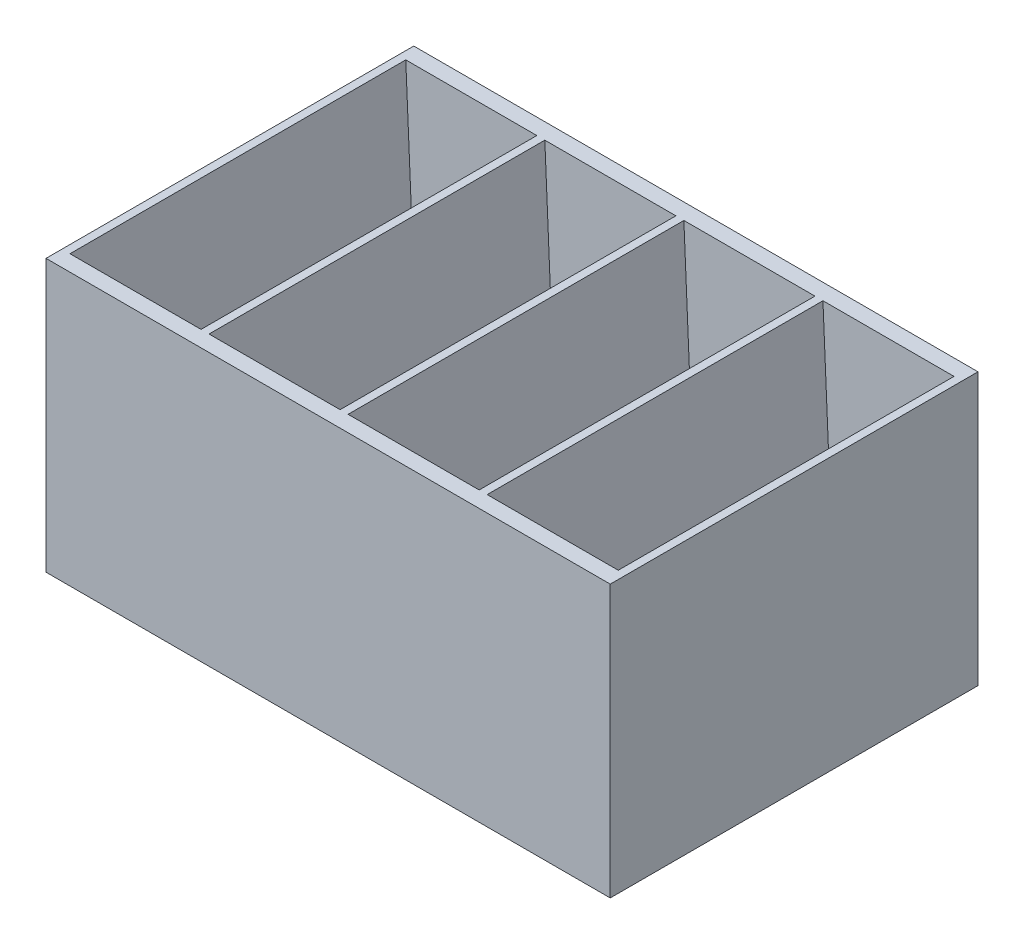
SolidWorks part; units mm, degrees
ref_plane "Front Plane" through (0, 0, 0) normal (0, 0, 1) x (1, 0, 0)
ref_plane "Top Plane" through (0, 0, 0) normal (0, 1, 0) x (1, 0, 0)
ref_plane "Right Plane" through (0, 0, 0) normal (1, 0, 0) x (0, 0, -1)
sketch "Sketch1" plane through (0, 0, 0) normal (0, 0, 1) x (1, 0, 0)
  line L0 (0, 0) -> (0, 107.95)
  line L1 (0, 0) -> (224.0826, 0) construction
  line L2 (0, 0) -> (0, 107.95) construction
  line L3 (0, 107.95) -> (224.0826, 107.95) construction
  line L4 (7.611, 6.35) -> (7.611, 107.95) construction
  line L5 (0, 107.95) -> (3.175, 107.95)
  line L6 (3.175, 107.95) -> (7.611, 6.35)
  line L7 (7.611, 6.35) -> (50.791, 6.35)
  line L8 (50.791, 6.35) -> (55.2269, 107.95)
  line L9 (55.2269, 107.95) -> (55.2269, 0) construction
  line L10 (55.2269, 107.95) -> (58.4019, 107.95)
  line L11 (58.4019, 107.95) -> (58.4019, 0) construction
  line L12 (7.611, 107.95) -> (3.175, 107.95) construction
  line L13 (58.4019, 107.95) -> (62.8379, 6.35)
  line L14 (62.8379, 6.35) -> (106.0179, 6.35)
  line L15 (106.0179, 6.35) -> (110.4538, 107.95)
  line L16 (110.4538, 107.95) -> (113.6288, 107.95)
  line L17 (113.6288, 107.95) -> (118.0648, 6.35)
  line L18 (118.0648, 6.35) -> (161.2448, 6.35)
  line L19 (161.2448, 6.35) -> (165.6807, 107.95)
  line L20 (165.6807, 107.95) -> (168.8557, 107.95)
  line L21 (168.8557, 107.95) -> (173.2917, 6.35)
  line L22 (173.2917, 6.35) -> (216.4717, 6.35)
  line L23 (216.4717, 6.35) -> (220.9076, 107.95)
  line L24 (220.9076, 107.95) -> (224.0826, 107.95)
  line L25 (224.0826, 107.95) -> (224.0826, 0)
  line L26 (224.0826, 0) -> (0, 0)
  line L27 (110.4538, 107.95) -> (110.4538, 0) construction
  line L28 (113.6288, 107.95) -> (113.6288, 0) construction
  line L29 (165.6807, 107.95) -> (165.6807, 0) construction
  line L30 (168.8557, 107.95) -> (168.8557, 0) construction
  line L31 (50.791, 6.35) -> (62.8379, 6.35) construction
  line L32 (106.0179, 6.35) -> (118.0648, 6.35) construction
  line L33 (161.2448, 6.35) -> (173.2917, 6.35) construction
  line L34 (112.0413, 113.03) -> (112.0413, -30.1165) construction
  line L35 (-40.3587, 141.2445) -> (-40.3587, -34.167) construction
  line L36 (264.4413, 143.4606) -> (264.4413, -34.167) construction
  line L37 (50.791, 6.35) -> (50.791, 113.03) construction
  line L38 (92.9913, 151.13) -> (131.0913, 151.13) construction
  line L39 (92.9913, 151.13) -> (92.9913, 113.03) construction
  line L40 (92.9913, 113.03) -> (131.0913, 113.03) construction
  line L41 (131.0913, 151.13) -> (131.0913, 113.03) construction
  line L42 (12.691, 113.03) -> (50.791, 113.03) construction
  line L43 (12.691, 113.03) -> (12.691, 151.13) construction
  line L44 (12.691, 151.13) -> (50.791, 151.13) construction
  line L45 (50.791, 113.03) -> (50.791, 151.13) construction
  line L46 (71.8911, 162.5443) -> (71.8911, 143.1127) construction
  point P38 (112.0413, 113.03)
  point P43 (50.791, 113.03)
  point P45 (31.741, 151.13)
  point P46 (112.0413, 151.13)
  dimension "D1" = 52.0519
  dimension "D2" = 107.95
  dimension "D3" = 43.18
  dimension "D4" = 6.35
  dimension "D5" = 2.5
  dimension "D6" = 2.5
  dimension "D7" = 3.175
  dimension "D8" = 3.175
  dimension "D9" = 4.436
  dimension "D10" = 3.175
  dimension "D11" = 3.175
  dimension "D12" = 3.175
  dimension "D13" = 2.5
  dimension "D14" = 2.5
  dimension "D15" = 2.5
  dimension "D16" = 2.5
  dimension "D17" = 2.5
  dimension "D18" = 2.5
  dimension "D19" = 43.18
  dimension "D20" = 43.18
  dimension "D21" = 43.18
  dimension "D22" = 224.0826
  dimension "D23" = 112.0413
  dimension "D24" = 304.8
  dimension "D25" = 40.3587
  dimension "D26" = 40.3587
  dimension "D27" = 38.1
  dimension "D28" = 38.1
  dimension "D29" = 38.1
  dimension "D30" = 38.1
  dimension "D31" = 5.08
  dimension "D32" = 80.3004
  dimension "D33" = 40.1502
extrude "Boss-Extrude1" add sketch "Sketch1" along normal blind 146.05
sketch "Sketch2" plane through (0, 0, 146.05) normal (0, 0, 1) x (1, 0, 0)
  line L0 (3.175, 107.95) -> (55.2269, 107.95)
  line L1 (55.2269, 107.95) -> (50.791, 6.35)
  line L2 (50.791, 6.35) -> (7.611, 6.35)
  line L3 (7.611, 6.35) -> (3.175, 107.95)
  line L4 (58.4019, 107.95) -> (62.8379, 6.35)
  line L5 (62.8379, 6.35) -> (106.0179, 6.35)
  line L6 (106.0179, 6.35) -> (110.4538, 107.95)
  line L7 (110.4538, 107.95) -> (58.4019, 107.95)
  line L8 (113.6288, 107.95) -> (118.0648, 6.35)
  line L9 (118.0648, 6.35) -> (161.2448, 6.35)
  line L10 (161.2448, 6.35) -> (165.6807, 107.95)
  line L11 (165.6807, 107.95) -> (113.6288, 107.95)
  line L12 (168.8557, 107.95) -> (173.2917, 6.35)
  line L13 (173.2917, 6.35) -> (216.4717, 6.35)
  line L14 (216.4717, 6.35) -> (220.9076, 107.95)
  line L15 (220.9076, 107.95) -> (168.8557, 107.95)
extrude "Boss-Extrude2" add sketch "Sketch2" against normal blind 6.35
ref_plane "Plane1" through (0, 0, 73.025) normal (0, 0, -1) x (-1, 0, 0)
mirror "Mirror1" about plane through (0, 0, 73.025) normal (0, 0, -1) of "Boss-Extrude2"
ref_plane "Plane2" through (112.0413, 0, 0) normal (1, 0, 0) x (0, 0, -1)
equation "\"D8@Sketch1\"=\"D7@Sketch1\""
equation "\"D10@Sketch1\"=\"D8@Sketch1\""
equation "\"D11@Sketch1\"=\"D7@Sketch1\""
equation "\"D12@Sketch1\"=\"D7@Sketch1\""
equation "\"D13@Sketch1\"=\"D5@Sketch1\""
equation "\"D6@Sketch1\"=\"D5@Sketch1\""
equation "\"D14@Sketch1\"=\"D5@Sketch1\""
equation "\"D15@Sketch1\"=\"D5@Sketch1\""
equation "\"D16@Sketch1\"=\"D5@Sketch1\""
equation "\"D17@Sketch1\"=\"D5@Sketch1\""
equation "\"D18@Sketch1\"=\"D5@Sketch1\""
equation "\"D19@Sketch1\"=\"D3@Sketch1\""
equation "\"D20@Sketch1\"=\"D3@Sketch1\""
equation "\"D21@Sketch1\"=\"D3@Sketch1\""
equation "\"D23@Sketch1\"=\"D22@Sketch1\"/2"
equation "\"D25@Sketch1\"=(\"D24@Sketch1\"-\"D22@Sketch1\")/2"
equation "\"D33@Sketch1\"=\"D32@Sketch1\"/2"
